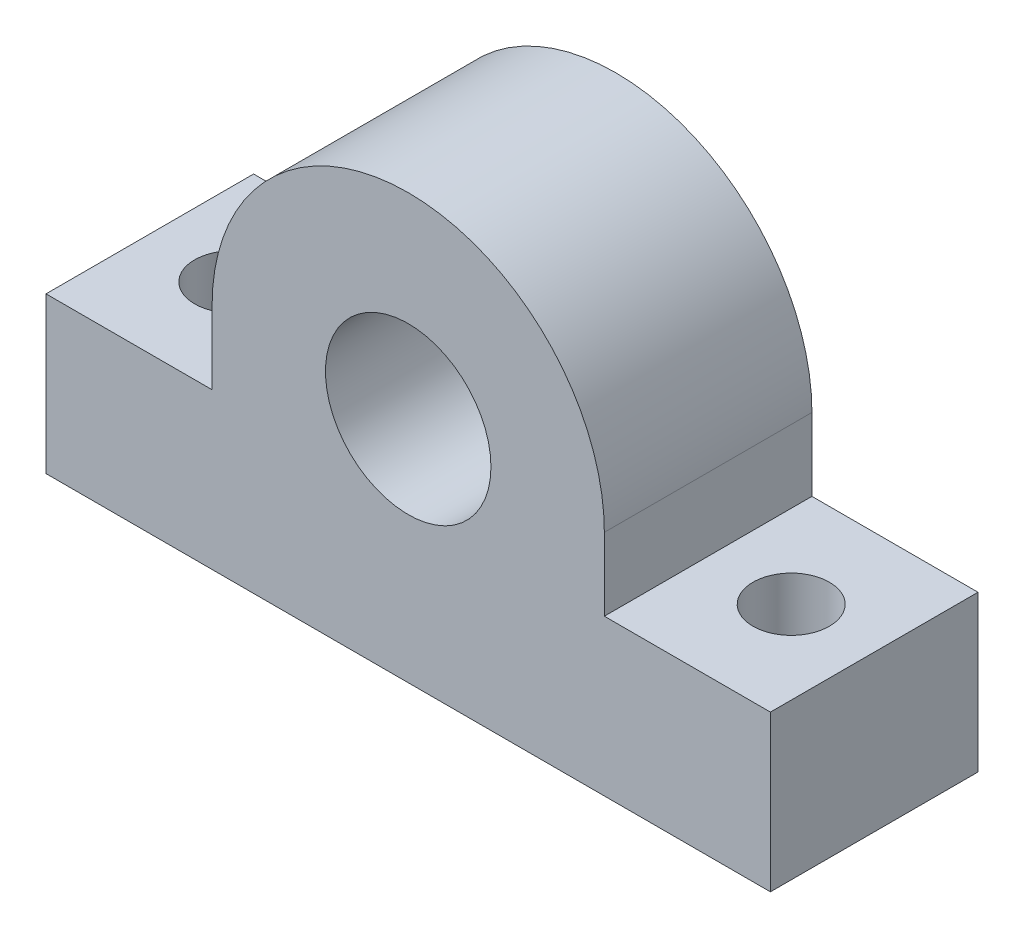
SolidWorks part; units mm, degrees
ref_plane "Front Plane" through (0, 0, 0) normal (0, 0, 1) x (1, 0, 0)
ref_plane "Top Plane" through (0, 0, 0) normal (0, 1, 0) x (1, 0, 0)
ref_plane "Right Plane" through (0, 0, 0) normal (1, 0, 0) x (0, 0, -1)
sketch "Sketch1" plane through (0, 0, 0) normal (0, 0, 1) x (1, 0, 0)
  line L0 (-6, 0) -> (-6, -2.2225)
  line L1 (6, 0) -> (6, -2.2225)
  line L2 (-11.08, -6.985) -> (11.08, -6.985)
  line L4 (-11.08, -6.985) -> (-11.08, -2.2225)
  line L5 (-11.08, -2.2225) -> (-6, -2.2225)
  line L7 (11.08, -6.985) -> (11.08, -2.2225)
  line L8 (11.08, -2.2225) -> (6, -2.2225)
  circle A0 centre (0, 0) radius 2.5312
  arc A1 (6, 0) -> (-6, 0) centre (0, 0) ccw
  dimension "D1" = 5.0625
  dimension "D2" = 12
extrude "Boss-Extrude1" add sketch "Sketch1" along normal blind 6.35
sketch "Sketch2" plane through (0, -2.2225, 0) normal (0, 1, 0) x (1, 0, 0)
  circle A0 centre (-8.54, -3.175) radius 1.1684
  circle A1 centre (8.54, -3.175) radius 1.1684
extrude "Cut-Extrude1" cut sketch "Sketch2" against normal blind 6.35
sketch "Sketch3" plane through (0, -6.985, 0) normal (0, -1, 0) x (1, 0, 0)
  line L4 (-11.08, 0) -> (11.08, 0)
  line L5 (11.08, 0) -> (11.08, 6.35)
  line L6 (11.08, 6.35) -> (-11.08, 6.35)
  line L7 (-11.08, 6.35) -> (-11.08, 0)
  line L8 (-11.08, 0) -> (11.08, 0)
  line L9 (11.08, 0) -> (11.08, 6.35)
  line L10 (11.08, 6.35) -> (-11.08, 6.35)
  line L11 (-11.08, 6.35) -> (-11.08, 0)
  circle A0 centre (8.54, 3.175) radius 1.1684 construction
  dimension "D2" = 2.54
  dimension "D3" = 22.16
  dimension "D1" = 0
